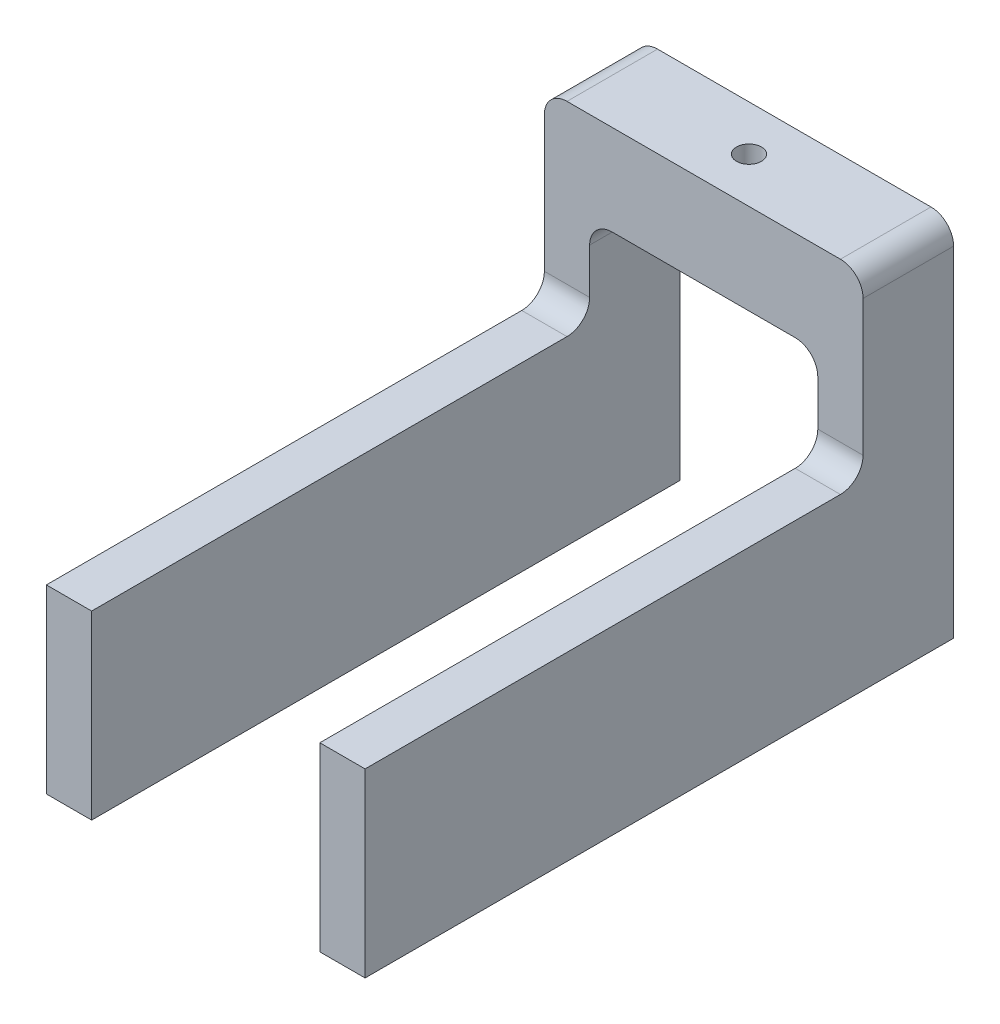
SolidWorks part; units mm, degrees
ref_plane "Front Plane" through (0, 0, 0) normal (0, 0, 1) x (1, 0, 0)
ref_plane "Top Plane" through (0, 0, 0) normal (0, 1, 0) x (1, 0, 0)
ref_plane "Right Plane" through (0, 0, 0) normal (1, 0, 0) x (0, 0, -1)
sketch "Sketch1" plane through (0, 0, 0) normal (1, 0, 0) x (0, 0, -1)
  line L0 (0, 0) -> (-165.1, 0)
  line L1 (-165.1, 0) -> (-165.1, 50.8)
  line L2 (-165.1, 50.8) -> (-25.4, 50.8)
  line L3 (-25.4, 50.8) -> (-25.4, 101.6)
  line L4 (-25.4, 101.6) -> (0, 101.6)
  line L5 (0, 101.6) -> (0, 0)
  point P7 (-12.7, 101.6)
  dimension "D1" = 152.4
  dimension "D2" = 50.8
  dimension "D3" = 101.6
  dimension "D4" = 25.4
extrude "Boss-Extrude1" add sketch "Sketch1" along normal blind 89.408
sketch "Sketch2" plane through (0, 0, 0) normal (0, 0, -1) x (-1, 0, 0)
  line L0 (-89.408, 0) -> (0, 0) construction
  line L1 (-76.708, 0) -> (-76.708, 76.2)
  line L2 (-76.708, 76.2) -> (-12.7, 76.2)
  line L3 (-12.7, 76.2) -> (-12.7, 0)
  line L4 (-12.7, 0) -> (-76.708, 0)
  line L5 (-89.408, 0) -> (-89.408, 101.6) construction
  line L6 (0, 0) -> (0, 101.6) construction
  line L7 (-89.408, 101.6) -> (0, 101.6) construction
  dimension "D1" = 12.7
  dimension "D2" = 12.7
  dimension "D3" = 25.4
extrude "Cut-Extrude1" cut sketch "Sketch2" against normal through all
hole_wizard "Ø7.0mm Dowel Hole1" positions "Sketch3" profile "Sketch4" hole size "Ø1.0" standard "ANSI Metric" end condition through all
sketch "Sketch3" plane through (0, 101.6, 0) normal (0, 1, 0) x (1, 0, 0)
  point P0 (44.704, -12.7)
  dimension "D1" = 44.704
  dimension "D2" = 12.7
sketch "Sketch4" plane through (44.704, 101.6, 12.7) normal (1, 0, 0) x (0, 0, 1)
  line L0 (0, 0) -> (0, 101.6)
  line L1 (0, 101.6) -> (3.5, 101.6)
  line L2 (3.5, 101.6) -> (3.5, 0)
  line L5 (3.5, 0) -> (0, 0)
  line L11 (0, -6.35) -> (0, 107.95) construction
  dimension "Thru Hole Dia." = 7
  dimension "Thru Hole Depth" = 101.6
fillet "Fillet1" radius 6.35 6 edges at (76.708, 76.2, 12.7) (12.7, 76.2, 12.7) (6.35, 50.8, 25.4) (83.058, 50.8, 25.4) (89.408, 101.6, 12.7) (0, 101.6, 12.7)
